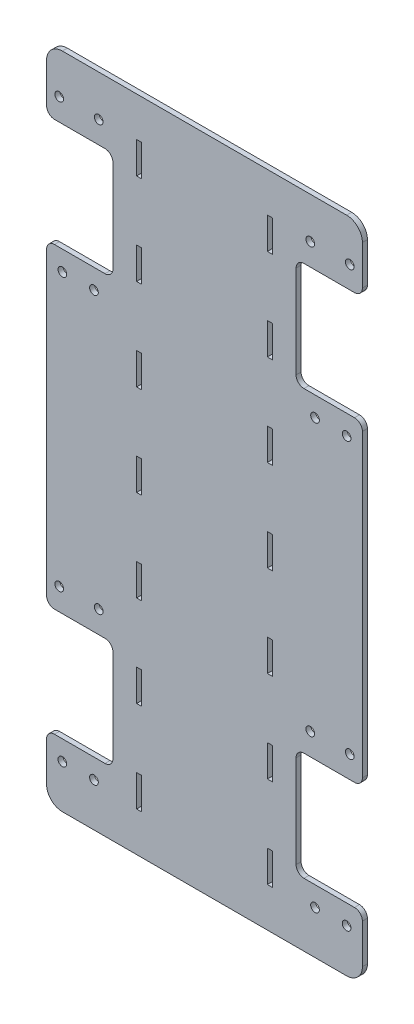
SolidWorks part; units mm, degrees
ref_plane "Plan de face" through (0, 0, 0) normal (0, 0, 1) x (1, 0, 0)
ref_plane "Plan de dessus" through (0, 0, 0) normal (0, 1, 0) x (1, 0, 0)
ref_plane "Plan de droite" through (0, 0, 0) normal (1, 0, 0) x (0, 0, -1)
sketch "Esquisse1" plane through (0, 0, 0) normal (0, 0, 1) x (1, 0, 0)
  line L0 (100, 208.6) -> (-100, 208.6)
  line L1 (-100, 208.6) -> (-100, 168.6)
  line L2 (-100, 168.6) -> (-58, 168.6)
  line L3 (-58, 168.6) -> (-58, 100)
  line L4 (-58, 100) -> (-100, 100)
  line L5 (-100, 100) -> (-100, -100)
  line L6 (-100, -100) -> (-58, -100)
  line L7 (-58, -100) -> (-58, -168.6)
  line L8 (-58, -168.6) -> (-100, -168.6)
  line L9 (-100, -168.6) -> (-100, -208.6)
  line L10 (-100, -208.6) -> (100, -208.6)
  line L11 (100, -208.6) -> (100, -168.6)
  line L12 (100, -168.6) -> (58, -168.6)
  line L13 (58, -168.6) -> (58, -100)
  line L14 (58, -100) -> (100, -100)
  line L15 (100, -100) -> (100, 100)
  line L16 (100, 100) -> (58, 100)
  line L17 (58, 100) -> (58, 168.6)
  line L18 (58, 168.6) -> (100, 168.6)
  line L19 (100, 168.6) -> (100, 208.6)
  point P17 (0, 208.6)
  point P22 (-100, 0)
  point P24 (-100, 188.6)
  dimension "D1" = 68.6
  dimension "D2" = 42
  dimension "D3" = 42
  dimension "D4" = 200
  dimension "D5" = 200
  dimension "D6" = 68.6
  dimension "D8" = 40
  dimension "D7" = 40
  dimension "D9" = 417.2
extrude "Boss.-Extru.1" add sketch "Esquisse1" along normal blind 3.175
sketch "Esquisse2" plane through (0, 0, 3.175) normal (0, 0, 1) x (1, 0, 0)
  line L0 (100, 208.6) -> (-100, 208.6) construction
  line L1 (-43, 183.6) -> (-39.825, 183.6)
  line L2 (-43, 183.6) -> (-43, 163.6)
  line L3 (-43, 163.6) -> (-39.825, 163.6)
  line L4 (-39.825, 183.6) -> (-39.825, 163.6)
  line L9 (-58, 168.6) -> (-58, 100) construction
  line L44 (-43, 125.7333) -> (-43, 105.7333)
  line L45 (-43, 125.7333) -> (-39.825, 125.7333)
  line L46 (-39.825, 125.7333) -> (-39.825, 105.7333)
  line L47 (-43, 105.7333) -> (-39.825, 105.7333)
  line L48 (-43, 67.8667) -> (-43, 47.8667)
  line L49 (-43, 67.8667) -> (-39.825, 67.8667)
  line L50 (-39.825, 67.8667) -> (-39.825, 47.8667)
  line L51 (-43, 47.8667) -> (-39.825, 47.8667)
  line L52 (-43, 10) -> (-43, -10)
  line L53 (-43, 10) -> (-39.825, 10)
  line L54 (-39.825, 10) -> (-39.825, -10)
  line L55 (-43, -10) -> (-39.825, -10)
  line L56 (-43, -47.8667) -> (-43, -67.8667)
  line L57 (-43, -47.8667) -> (-39.825, -47.8667)
  line L58 (-39.825, -47.8667) -> (-39.825, -67.8667)
  line L59 (-43, -67.8667) -> (-39.825, -67.8667)
  line L60 (-43, -105.7333) -> (-43, -125.7333)
  line L61 (-43, -105.7333) -> (-39.825, -105.7333)
  line L62 (-39.825, -105.7333) -> (-39.825, -125.7333)
  line L63 (-43, -125.7333) -> (-39.825, -125.7333)
  line L64 (-43, -163.6) -> (-43, -183.6)
  line L65 (-43, -163.6) -> (-39.825, -163.6)
  line L66 (-39.825, -163.6) -> (-39.825, -183.6)
  line L67 (-43, -183.6) -> (-39.825, -183.6)
  line L69 (-100, -208.6) -> (100, -208.6) construction
  dimension "D1" = 25
  dimension "D2" = 15
  dimension "D3" = 20
  dimension "D6" = 25
  dimension "D4" = 3.175
  dimension "D5" = 7
extrude "Enlèv. mat.-Extru.1" cut sketch "Esquisse2" against normal through all both and the other way through all
mirror "Symétrie1" about plane through (0, 0, 0) normal (1, 0, 0) of "Enlèv. mat.-Extru.1"
hole_wizard "Dégagement M51" positions "Esquisse3D1" profile "Esquisse4" hole size "M5" standard "Ansi Metric" end condition through all
sketch3d "Esquisse3D1"
  line L0 (-100, 168.6, 3.175) -> (-58, 168.6, 3.175) construction
  line L5 (-100, -100, 3.175) -> (-58, -100, 3.175) construction
  line L6 (-100, 208.6, 3.175) -> (-100, 168.6, 3.175) construction
  line L7 (100, 168.6, 3.175) -> (100, 208.6, 3.175) construction
  line L8 (-58, 100, 3.175) -> (-100, 100, 3.175) construction
  line L9 (-100, 100, 3.175) -> (-100, -100, 3.175) construction
  line L10 (100, -100, 3.175) -> (100, 100, 3.175) construction
  line L11 (-58, -168.6, 3.175) -> (-100, -168.6, 3.175) construction
  point P0 (90, -181.1, 3.175)
  point P2 (70, -181.1, 3.175)
  point P4 (-90, -181.1, 3.175)
  point P6 (-70, -181.1, 3.175)
  point P8 (-92, -86, 3.175)
  point P10 (-67, -86, 3.175)
  point P12 (67, -86, 3.175)
  point P14 (92, -86, 3.175)
  point P16 (70, 87.5, 3.175)
  point P22 (90, 87.5, 3.175)
  point P26 (67, 182.6, 3.175)
  point P28 (92, 182.6, 3.175)
  point P30 (-90, 87.5, 3.175)
  point P32 (-70, 87.5, 3.175)
  point P34 (-92, 182.6, 3.175)
  point P36 (-67, 182.6, 3.175)
  dimension "D4" = 25
  dimension "D1" = 14
  dimension "D2" = 25
  dimension "D5" = 14
  dimension "D3" = 8
  dimension "D6" = 8
  dimension "D7" = 12.5
  dimension "D8" = 20
  dimension "D9" = 10
  dimension "D10" = 10
  dimension "D11" = 20
  dimension "D12" = 12.5
sketch "Esquisse4" plane through (90, -181.1, 3.175) normal (1, 0, 0) x (0, -1, 0)
  line L0 (0, 0) -> (0, 3.175)
  line L1 (0, 3.175) -> (2.75, 3.175)
  line L2 (2.75, 3.175) -> (2.75, 0)
  line L5 (2.75, 0) -> (0, 0)
  line L11 (0, -6.35) -> (0, 107.95) construction
  dimension "Diamètre du perçage jusqu'au prochain" = 5.5
  dimension "Profondeur du perçage jusqu'au prochain" = 3.175
fillet "Congé1" radius 5 16 edges at (-100, 168.6, 1.5875) (100, 168.6, 1.5875) (100, 100, 1.5875) (58, 100, 1.5875) (58, 168.6, 1.5875) (58, -100, 1.5875) (100, -168.6, 1.5875) (100, -100, 1.5875) (58, -168.6, 1.5875) (-58, 100, 1.5875) (-58, 168.6, 1.5875) (-58, -100, 1.5875) (-58, -168.6, 1.5875) (-100, -168.6, 1.5875) (-100, -100, 1.5875) (-100, 100, 1.5875)
fillet "Congé2" radius 10 4 edges at (100, -208.6, 1.5875) (-100, -208.6, 1.5875) (-100, 208.6, 1.5875) (100, 208.6, 1.5875)
equation "\"D3@Esquisse1\"=\"D2@Esquisse1\""
equation "\"D6@Esquisse1\"=\"D1@Esquisse1\""
equation "\"D6@Esquisse2\"=\"D1@Esquisse2\""
equation "\"EpaisseurBois\"= 3.175mm"
equation "\"D4@Esquisse3D1\"=\"D2@Esquisse3D1\""
equation "\"D5@Esquisse3D1\"=\"D1@Esquisse3D1\""
equation "\"D6@Esquisse3D1\"=\"D3@Esquisse3D1\""
equation "\"D10@Esquisse3D1\"=\"D9@Esquisse3D1\""
equation "\"D11@Esquisse3D1\"=\"D8@Esquisse3D1\""
equation "\"D12@Esquisse3D1\"=\"D7@Esquisse3D1\""
